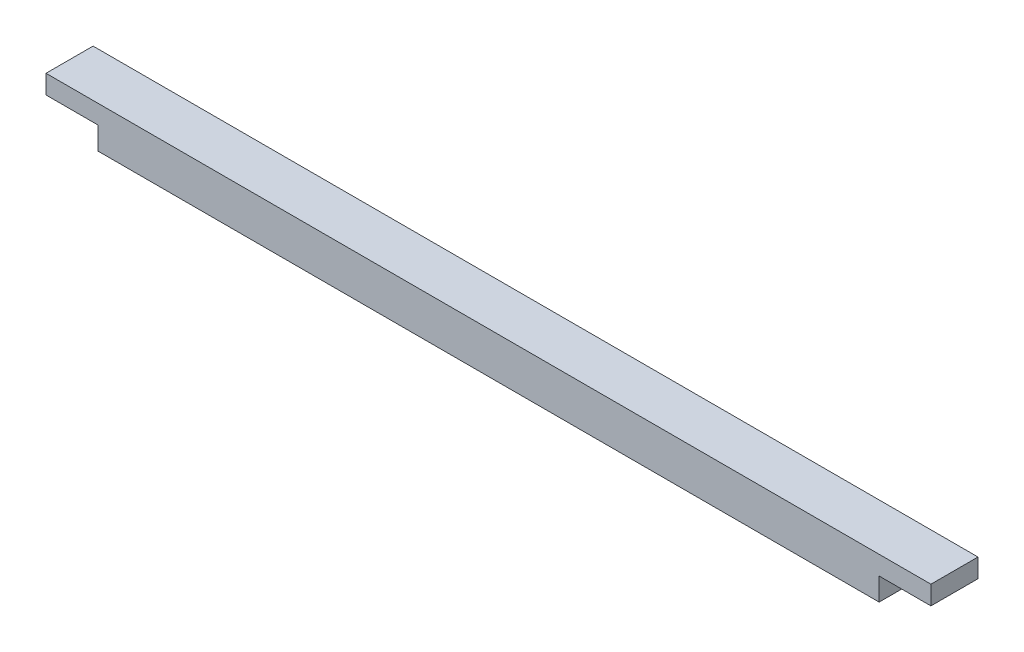
SolidWorks part; units mm, degrees
material "Сосна"
ref_plane "Спереди" through (0, 0, 0) normal (0, 0, 1) x (1, 0, 0)
ref_plane "Сверху" through (0, 0, 0) normal (0, 1, 0) x (1, 0, 0)
ref_plane "Справа" through (0, 0, 0) normal (1, 0, 0) x (0, 0, -1)
sketch "Эскиз1" plane through (0, 0, 0) normal (0, 1, 0) x (1, 0, 0)
  line L1 (0, 0) -> (470, 0)
  line L2 (0, 0) -> (0, 25)
  line L3 (0, 25) -> (470, 25)
  line L4 (470, 0) -> (470, 25)
  dimension "D1" = 470
  dimension "D2" = 25
extrude "Бобышка-Вытянуть1" add sketch "Эскиз1" along normal blind 22
sketch "Эскиз2" plane through (0, 0, 0) normal (0, 0, 1) x (1, 0, 0)
  line L7 (470, 0) -> (442.5, 0)
  line L8 (470, 0) -> (470, 12)
  line L9 (470, 12) -> (442.5, 12)
  line L10 (442.5, 0) -> (442.5, 12)
  dimension "D1" = 12
  dimension "D2" = 27.5
extrude "Вырез-Вытянуть1" cut sketch "Эскиз2" against normal through all
sketch "Эскиз3" plane through (0, 0, 0) normal (0, 0, 1) x (1, 0, 0)
  line L1 (0, 0) -> (27.5, 0)
  line L2 (0, 0) -> (0, 12)
  line L3 (0, 12) -> (27.5, 12)
  line L4 (27.5, 0) -> (27.5, 12)
  dimension "D1" = 12
  dimension "D2" = 27.5
extrude "Вырез-Вытянуть2" cut sketch "Эскиз3" against normal through all
